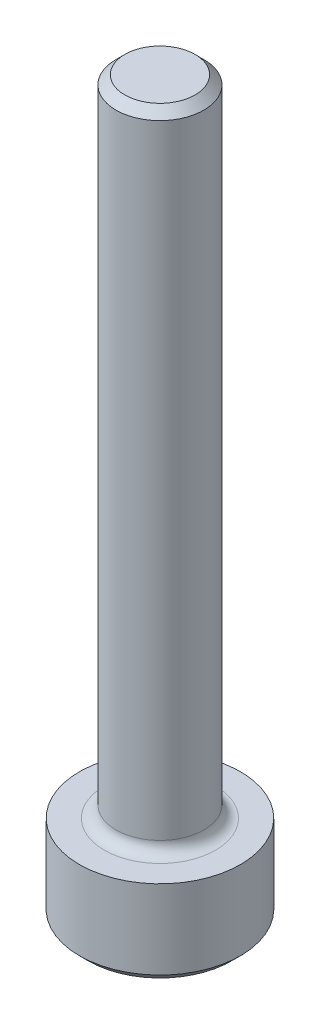
SolidWorks part; units mm, degrees
ref_plane "Front Plane" through (0, 0, 0) normal (0, 0, 1) x (1, 0, 0)
ref_plane "Top Plane" through (0, 0, 0) normal (0, 1, 0) x (1, 0, 0)
ref_plane "Right Plane" through (0, 0, 0) normal (1, 0, 0) x (0, 0, -1)
sketch "Sketch2" plane through (0, 0, 0) normal (0, 1, 0) x (1, 0, 0)
  circle A0 centre (0, 0) radius 1.5
extrude "Boss-Extrude1" add sketch "Sketch2" along normal blind 22
sketch "Sketch3" plane through (0, 0, 0) normal (0, 1, 0) x (1, 0, 0)
  circle A0 centre (0, 0) radius 2.75
  dimension "D1" = 5.5
extrude "Boss-Extrude2" add sketch "Sketch3" against normal blind 3
fillet "Fillet1" radius 0.4 1 edges at (0, 0, 1.5)
chamfer "Chamfer1" distance 0.3 angle 45 2 edges at (0, 22, 1.5) (0, -3, 2.75)
sketch "Sketch4" plane through (0, -3, 0) normal (0, -1, 0) x (1, 0, 0)
  line L1 (0, 1.4434) -> (-1.25, 0.7217)
  line L2 (-1.25, 0.7217) -> (-1.25, -0.7217)
  line L3 (-1.25, -0.7217) -> (0, -1.4434)
  line L4 (0, -1.4434) -> (1.25, -0.7217)
  line L5 (1.25, -0.7217) -> (1.25, 0.7217)
  line L6 (1.25, 0.7217) -> (0, 1.4434)
  circle A0 centre (0, 0) radius 1.25 construction
  dimension "D1" = 2.5
extrude "Cut-Extrude1" cut sketch "Sketch4" against normal blind 2.5
